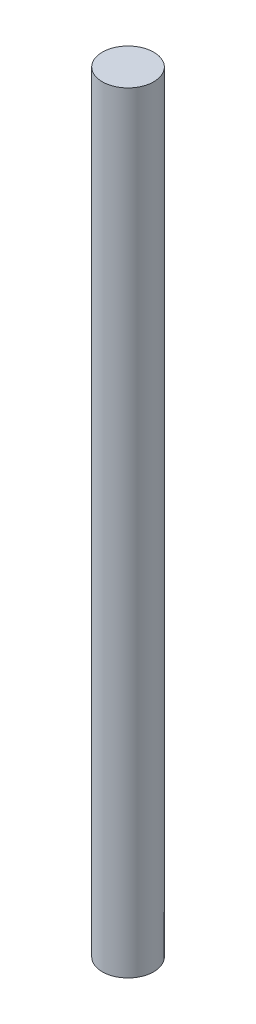
SolidWorks part; units mm, degrees
ref_plane "Front Plane" through (0, 0, 0) normal (0, 0, 1) x (1, 0, 0)
ref_plane "Top Plane" through (0, 0, 0) normal (0, 1, 0) x (1, 0, 0)
ref_plane "Right Plane" through (0, 0, 0) normal (1, 0, 0) x (0, 0, -1)
sketch "Sketch2" plane through (0, 0, 0) normal (0, 1, 0) x (1, 0, 0)
  circle A0 centre (0, 0) radius 6
  dimension "D1" = 12
extrude "Boss-Extrude1" add sketch "Sketch2" along normal mid plane 180
